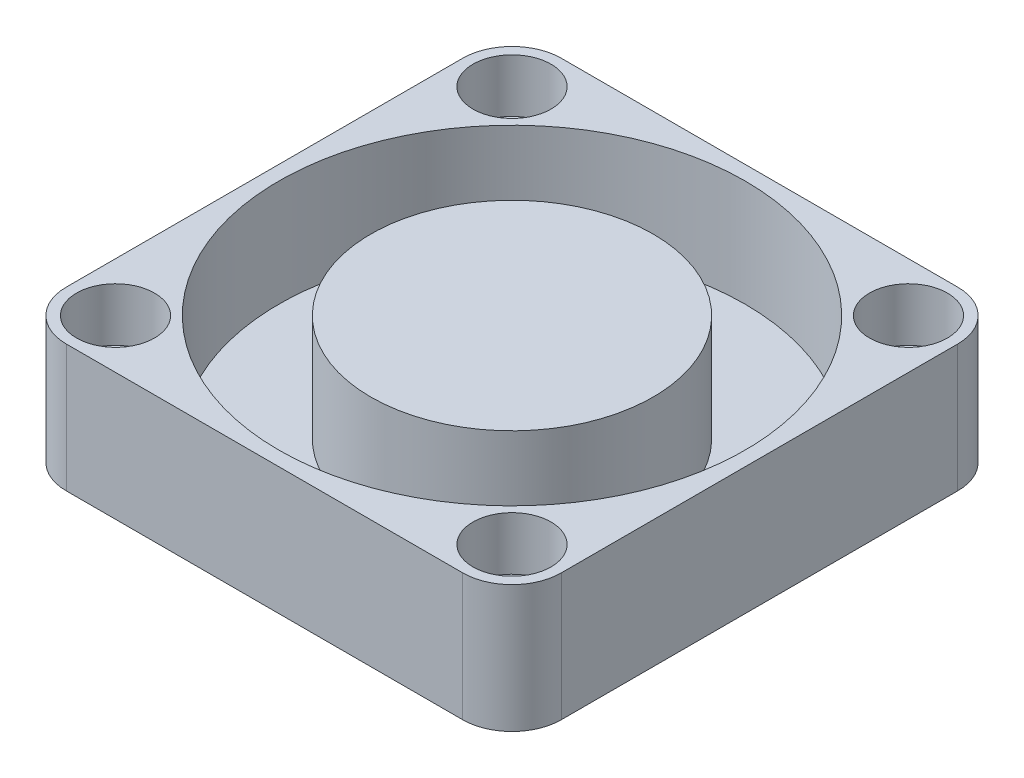
SolidWorks part; units mm, degrees
ref_plane "Front Plane" through (0, 0, 0) normal (0, 0, 1) x (1, 0, 0)
ref_plane "Top Plane" through (0, 0, 0) normal (0, 1, 0) x (1, 0, 0)
ref_plane "Right Plane" through (0, 0, 0) normal (1, 0, 0) x (0, 0, -1)
sketch "Sketch1" plane through (0, 0, 0) normal (0, 1, 0) x (1, 0, 0)
  line L1 (-15.075, -15.075) -> (15.075, -15.075)
  line L2 (-15.075, -15.075) -> (-15.075, 15.075)
  line L3 (-15.075, 15.075) -> (15.075, 15.075)
  line L4 (15.075, -15.075) -> (15.075, 15.075)
  line L5 (-15.075, -15.075) -> (15.075, 15.075) construction
  line L6 (-15.075, 15.075) -> (15.075, -15.075) construction
  point P0 (0, 0)
  dimension "D1" = 30.15
extrude "Boss-Extrude1" add sketch "Sketch1" along normal blind 7.75
fillet "Fillet1" radius 3 4 edges at (15.075, 3.875, -15.075) (-15.075, 3.875, -15.075) (-15.075, 3.875, 15.075) (15.075, 3.875, 15.075)
hole_wizard "M3 Clearance Hole1" positions "Sketch2" profile "Sketch3" hole size "M3" standard "ANSI Metric" end condition through all
sketch "Sketch2" plane through (0, 7.75, 0) normal (0, 1, 0) x (1, 0, 0)
  arc A0 (-12.075, 15.075) -> (-15.075, 12.075) centre (-12.075, 12.075) ccw construction
  arc A1 (-15.075, -12.075) -> (-12.075, -15.075) centre (-12.075, -12.075) ccw construction
  arc A2 (12.075, -15.075) -> (15.075, -12.075) centre (12.075, -12.075) ccw construction
  arc A3 (15.075, 12.075) -> (12.075, 15.075) centre (12.075, 12.075) ccw construction
  point P0 (-12.075, 12.075)
  point P2 (12.075, 12.075)
  point P4 (12.075, -12.075)
  point P6 (-12.075, -12.075)
sketch "Sketch3" plane through (-12.075, 7.75, -12.075) normal (1, 0, 0) x (0, 0, 1)
  line L0 (0, 0) -> (0, 7.75)
  line L1 (0, 7.75) -> (1.6, 7.75)
  line L2 (1.6, 7.75) -> (1.6, 0)
  line L5 (1.6, 0) -> (0, 0)
  line L11 (0, -6.35) -> (0, 107.95) construction
  dimension "Thru Hole Dia." = 3.2
  dimension "Thru Hole Depth" = 7.75
sketch "Sketch4" plane through (0, 7.75, 0) normal (0, 1, 0) x (1, 0, 0)
  circle A0 centre (-12.075, 12.075) radius 2.375
  circle A1 centre (12.075, 12.075) radius 2.375
  circle A2 centre (-12.075, -12.075) radius 2.375
  circle A3 centre (12.075, -12.075) radius 2.375
  dimension "D1" = 4.75
extrude "Cut-Extrude1" cut sketch "Sketch4" against normal blind 3.25
sketch "Sketch5" plane through (0, 7.75, 0) normal (0, 1, 0) x (1, 0, 0)
  circle A0 centre (0, 0) radius 14.2
  circle A1 centre (0, 0) radius 8.6
  dimension "D1" = 28.4
  dimension "D2" = 17.2
extrude "Cut-Extrude2" cut sketch "Sketch5" against normal blind 6.5
